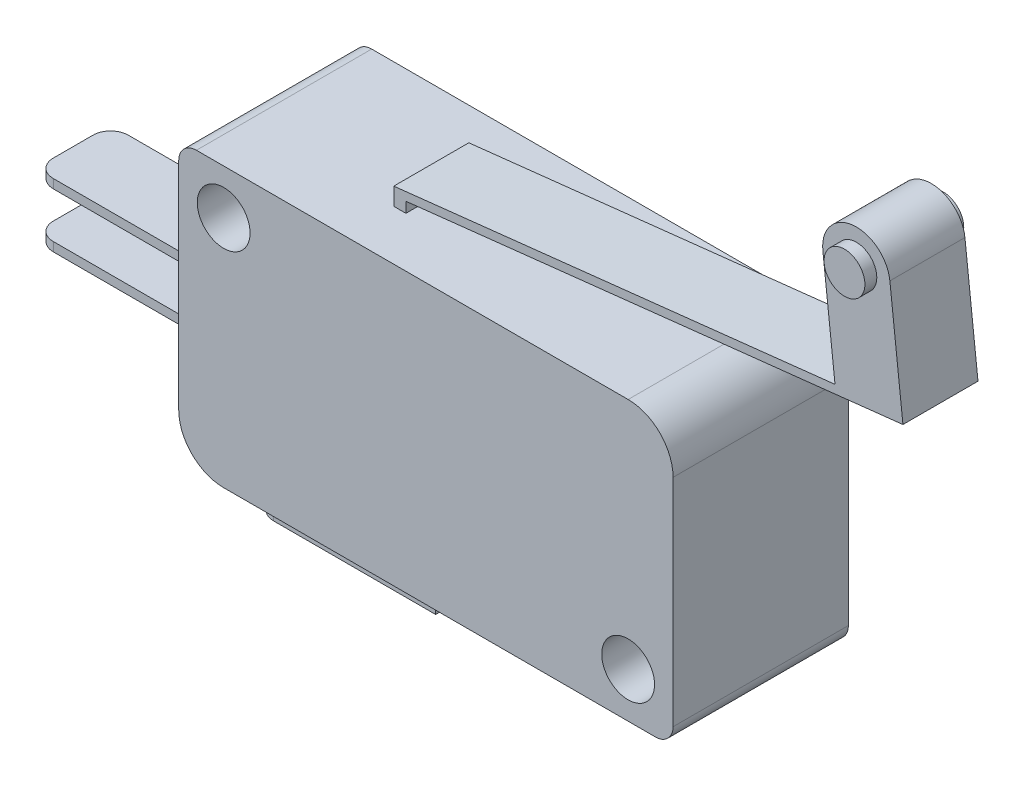
SolidWorks part; units mm, degrees
ref_plane "Front Plane" through (0, 0, 0) normal (0, 0, 1) x (1, 0, 0)
ref_plane "Top Plane" through (0, 0, 0) normal (0, 1, 0) x (1, 0, 0)
ref_plane "Right Plane" through (0, 0, 0) normal (1, 0, 0) x (0, 0, -1)
sketch "Sketch1" plane through (0, 0, 0) normal (0, 0, 1) x (1, 0, 0)
  line L1 (0, 0) -> (27.94, 0)
  line L2 (0, 0) -> (0, 15.748)
  line L3 (0, 15.748) -> (27.94, 15.748)
  line L4 (27.94, 0) -> (27.94, 15.748)
  dimension "D1" = 27.94
  dimension "D2" = 15.748
extrude "Boss-Extrude1" add sketch "Sketch1" along normal blind 9.906
sketch "Sketch2" plane through (0, 0, 9.906) normal (0, 0, 1) x (1, 0, 0)
  line L0 (0, 15.748) -> (0, 0) construction
  line L1 (0, 13.208) -> (2.54, 13.208) construction
  line L2 (2.54, 13.208) -> (2.54, 15.748) construction
  line L3 (27.94, 15.748) -> (0, 15.748) construction
  line L5 (27.94, 0) -> (27.94, 15.748) construction
  line L6 (27.94, 2.54) -> (25.4, 2.54) construction
  line L7 (25.4, 2.54) -> (25.4, 0) construction
  line L8 (0, 0) -> (27.94, 0) construction
  circle A0 centre (2.54, 13.208) radius 1.4922
  circle A1 centre (25.4, 2.54) radius 1.4923
  dimension "D1" = 2.54
  dimension "D2" = 2.9845
extrude "Cut-Extrude1" cut sketch "Sketch2" against normal through all
fillet "Fillet1" radius 2.54 2 edges at (0, 0, 4.953) (27.94, 15.748, 4.953)
ref_plane "Plane1" through (0, 0, 4.953) normal (0, 0, 1) x (1, 0, 0)
sketch "Sketch3" plane through (0, 0, 4.953) normal (0, 0, 1) x (1, 0, 0)
  line L0 (9.3219, 15.748) -> (9.3219, 16.7363)
  line L1 (25.4, 15.748) -> (0, 15.748) construction
  line L2 (9.3219, 16.7363) -> (34.2613, 19.5035)
  line L3 (34.2613, 19.5035) -> (33.574, 25.6979)
  line L4 (33.574, 25.6979) -> (37.3608, 26.1181) construction
  line L5 (37.3608, 26.1181) -> (38.1, 19.4558)
  line L6 (38.1, 19.4558) -> (10.0082, 16.3388)
  line L7 (10.0082, 16.3388) -> (10.0082, 15.748)
  line L8 (10.0082, 15.748) -> (9.3219, 15.748)
  line L9 (11.1789, 0) -> (11.1789, -2.54)
  line L10 (2.54, 0) -> (27.94, 0) construction
  line L11 (11.1789, -2.54) -> (1.5269, -2.54)
  line L12 (1.5269, -2.54) -> (1.5269, -3.048)
  line L13 (1.5269, -3.048) -> (11.6869, -3.048)
  line L14 (11.6869, -3.048) -> (11.6869, 0)
  line L15 (27.94, 0) -> (27.94, 13.208) construction
  line L16 (0, 15.748) -> (0, 2.54) construction
  line L17 (0, 3.8959) -> (-10.922, 3.8959)
  line L18 (-10.922, 3.8959) -> (-10.922, 4.4039)
  line L19 (-10.922, 4.4039) -> (0, 4.4039)
  line L21 (0, 6.9796) -> (-10.922, 6.9796)
  line L22 (-10.922, 6.9796) -> (-10.922, 7.4876)
  line L23 (-10.922, 7.4876) -> (0, 7.4876)
  line L24 (0, 7.4876) -> (0, 6.9796)
  line L25 (0, 4.4039) -> (0, 3.8959)
  line L26 (11.1789, 0) -> (11.6869, 0)
  arc A0 (33.574, 25.6979) -> (37.3608, 26.1181) centre (35.4674, 25.908) cw
  dimension "D6" = 10.16
  dimension "D1" = 0.508
  dimension "D2" = 10.922
  dimension "D3" = 2.54
  dimension "D4" = 10.16
  dimension "D5" = 10.16
  dimension "D7" = 3.81
extrude "Boss-Extrude2" add sketch "Sketch3" along normal blind 2.1209 and the other way blind 2.1209
fillet "Fillet2" radius 1 8 edges at (-10.922, 7.2336, 2.8321) (-10.922, 4.1499, 2.8321) (1.5269, -2.794, 2.8321) (1.5269, -2.794, 7.0739) (-10.922, 4.1499, 7.0739) (-10.922, 7.2336, 7.0739) (27.94, 0, 4.953) (0, 15.748, 4.953)
sketch "Sketch4" plane through (0, 0, 4.953) normal (0, 0, 1) x (1, 0, 0)
  circle A0 centre (35.4674, 25.908) radius 1.155
  arc A1 (37.3608, 26.1181) -> (33.574, 25.6979) centre (35.4674, 25.908) ccw construction
  dimension "D1" = 0.75
extrude "Boss-Extrude3" add sketch "Sketch4" along normal blind 2.794 and the other way blind 2.794
